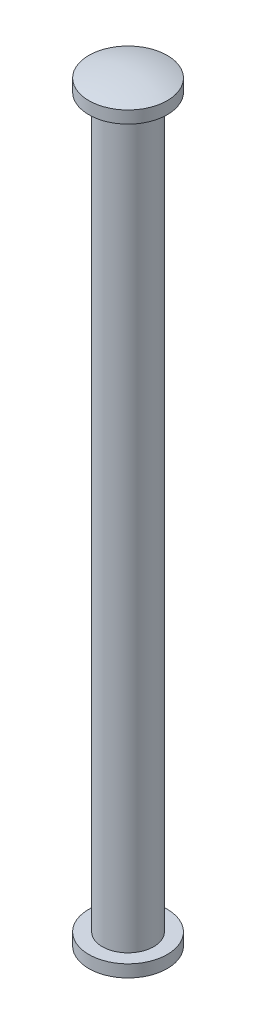
SolidWorks part; units mm, degrees
ref_plane "Front" through (0, 0, 0) normal (0, 0, 1) x (1, 0, 0)
ref_plane "Top" through (0, 0, 0) normal (0, 1, 0) x (1, 0, 0)
ref_plane "Right" through (0, 0, 0) normal (1, 0, 0) x (0, 0, -1)
sketch "Sketch1" plane through (0, 0, 0) normal (0, 0, 1) x (1, 0, 0)
  line L0 (0, -19.812) -> (0, 19.812)
  line L1 (0, 0) -> (1.3335, 0) construction
  line L2 (1.3335, -18.8431) -> (1.3335, 18.8431)
  line L3 (1.3335, 18.8431) -> (2.032, 18.8431)
  line L4 (2.032, 18.8431) -> (2.032, 19.4781)
  line L5 (2.032, -18.8431) -> (2.032, -19.4781)
  line L6 (1.3335, -18.8431) -> (2.032, -18.8431)
  arc A0 (2.032, 19.4781) -> (0, 19.812) centre (0, 13.462) ccw
  arc A1 (2.032, -19.4781) -> (0, -19.812) centre (0, -13.462) cw
  dimension "D1" = 1.3335
  dimension "D2" = 2.032
  dimension "D3" = 0.635
  dimension "D4" = 19.812
  dimension "D5" = 6.35
revolve "Revolve1" add sketch "Sketch1" angle 360 about L0
